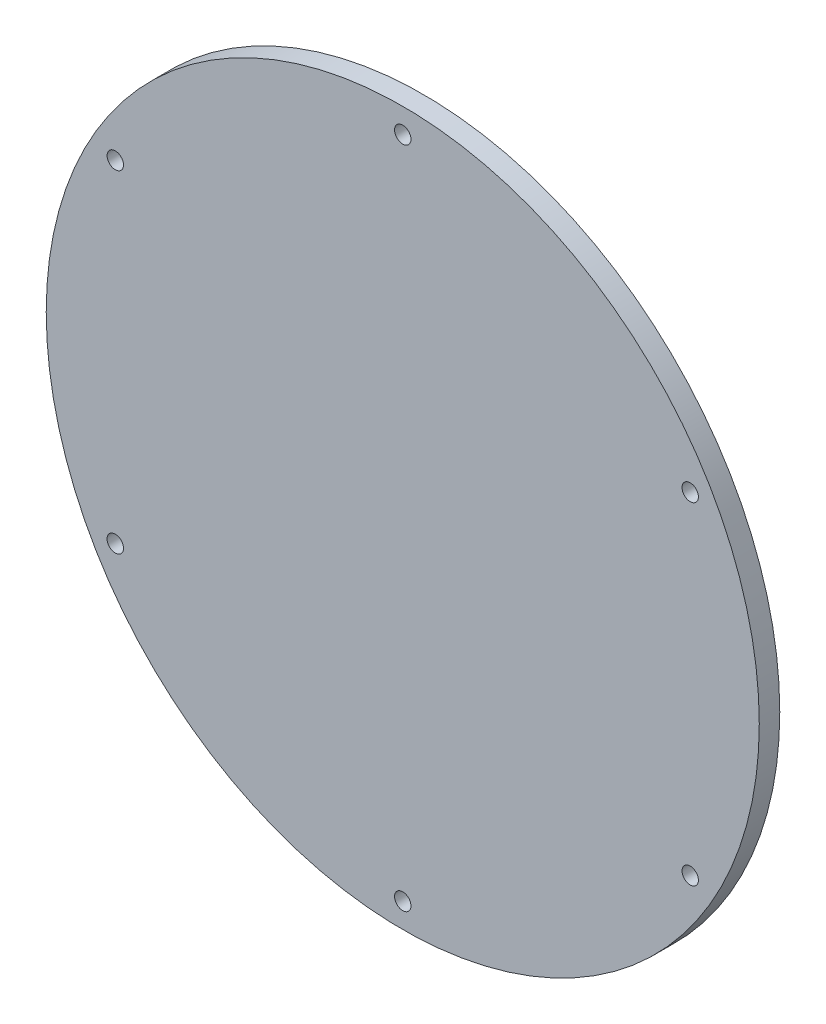
SolidWorks part; units mm, degrees
ref_plane "Front Plane" through (0, 0, 0) normal (0, 0, 1) x (1, 0, 0)
ref_plane "Top Plane" through (0, 0, 0) normal (0, 1, 0) x (1, 0, 0)
ref_plane "Right Plane" through (0, 0, 0) normal (1, 0, 0) x (0, 0, -1)
sketch "Sketch1" plane through (0, 0, 0) normal (0, 0, 1) x (1, 0, 0)
  line L0 (0, 174) -> (0, 162) construction
  circle A0 centre (0, 0) radius 174
  circle A1 centre (0, 162) radius 4
  circle A2 centre (140.2961, 81) radius 4
  circle A3 centre (140.2961, -81) radius 4
  circle A4 centre (0, -162) radius 4
  circle A5 centre (-140.2961, -81) radius 4
  circle A6 centre (-140.2961, 81) radius 4
  point P19 (0, 0)
  dimension "D1" = 348
  dimension "D3" = 8
  dimension "D2" = 12
  dimension "D4" = 6
extrude "Boss-Extrude1" add sketch "Sketch1" along normal blind 10
equation "\"acTubeOD\"= 300mm"
equation "\"acTubeThickness\"= 3mm"
equation "\"acTubeLength\"= 300mm"
equation "\"threadedRodDiam\"= 8mm"
equation "\"flange width\"= 24mm"
equation "\"D1@Sketch1\"=\"acTubeOD\" + \"flange width\"*2"
